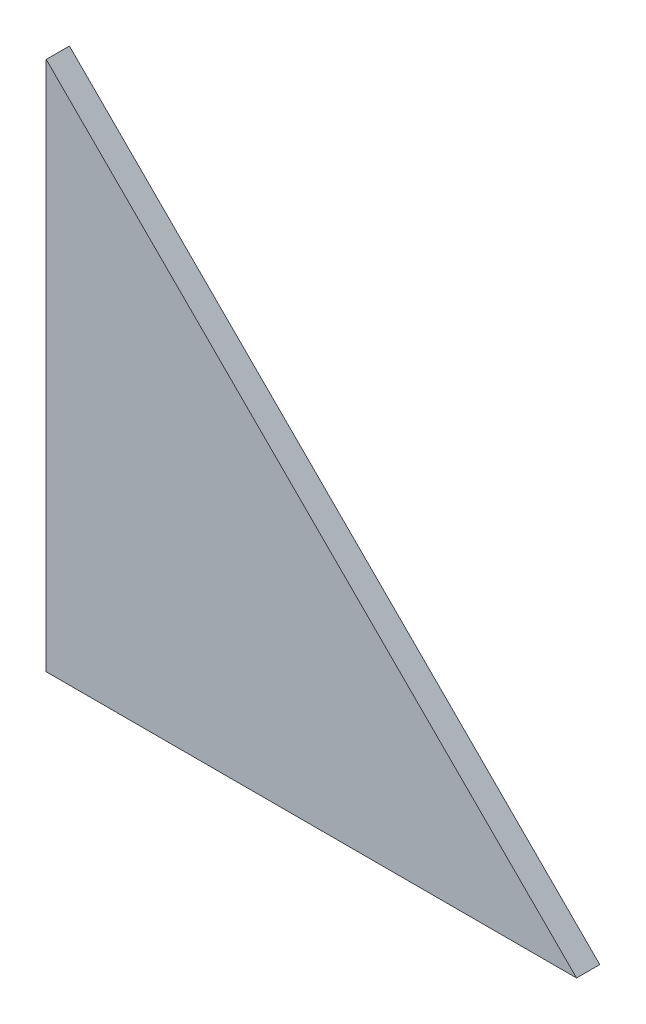
SolidWorks part; units mm, degrees
ref_plane "Front Plane" through (0, 0, 0) normal (0, 0, 1) x (1, 0, 0)
ref_plane "Top Plane" through (0, 0, 0) normal (0, 1, 0) x (1, 0, 0)
ref_plane "Right Plane" through (0, 0, 0) normal (1, 0, 0) x (0, 0, -1)
sketch "Sketch2" plane through (0, 0, 0) normal (0, 0, 1) x (1, 0, 0)
  line L0 (0, 0) -> (101.6, 0)
  line L1 (0, 0) -> (0, 101.6)
  line L2 (0, 101.6) -> (101.6, 0)
  dimension "D1" = 101.6
  dimension "D2" = 101.6
extrude "Boss-Extrude1" add sketch "Sketch2" along normal blind 4.445
